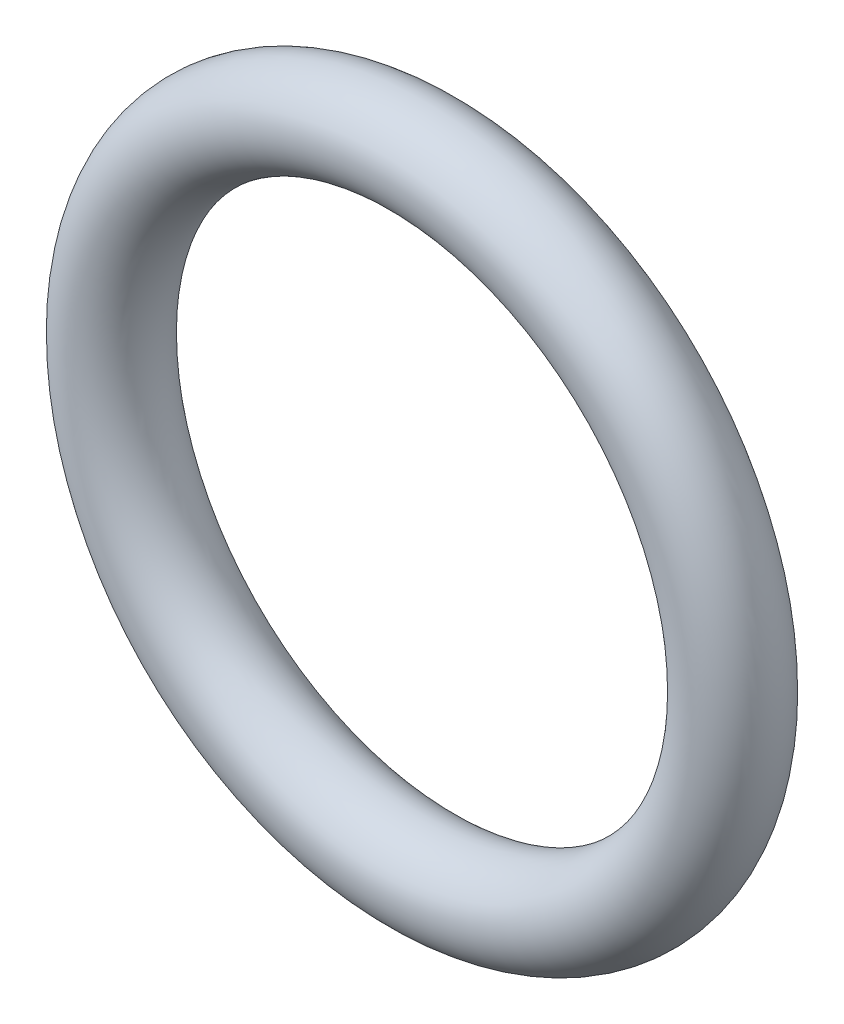
SolidWorks part; units mm, degrees
ref_plane "Front Plane" through (0, 0, 0) normal (0, 0, 1) x (1, 0, 0)
ref_plane "Top Plane" through (0, 0, 0) normal (0, 1, 0) x (1, 0, 0)
ref_plane "Right Plane" through (0, 0, 0) normal (1, 0, 0) x (0, 0, -1)
sketch "Sketch3" plane through (0, 0, 0) normal (0, 0, 1) x (1, 0, 0)
  circle A0 centre (0, 0) radius 13.5
  dimension "D1" = 27
sketch "Sketch4" plane through (0, 0, 0) normal (0, 1, 0) x (1, 0, 0)
  line L0 (-13.5, 0) -> (13.5, 0) construction
  circle A0 centre (-13.5, 0) radius 2
  dimension "D1" = 4
sweep "Sweep1" add profiles "Sketch4" path "Sketch3"
